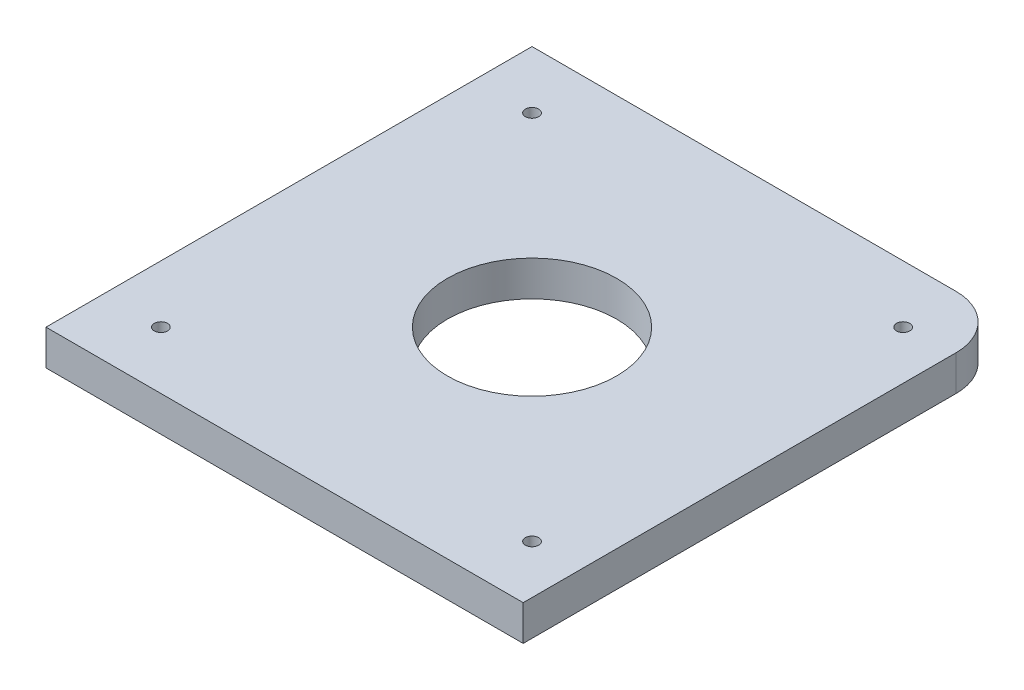
SolidWorks part; units mm, degrees
ref_plane "Front Plane" through (0, 0, 0) normal (0, 0, 1) x (1, 0, 0)
ref_plane "Top Plane" through (0, 0, 0) normal (0, 1, 0) x (1, 0, 0)
ref_plane "Right Plane" through (0, 0, 0) normal (1, 0, 0) x (0, 0, -1)
sketch "Sketch1" plane through (0, 0, 0) normal (0, 1, 0) x (1, 0, 0)
  line L2 (-55, -55) -> (-55, 55)
  line L3 (-55, 55) -> (53, 55)
  line L9 (-42, 55) -> (-42, -55) construction
  line L10 (53, 55) -> (53, -55)
  line L15 (42, 55) -> (42, -55) construction
  line L16 (53, -55) -> (-55, -55)
  circle A16 centre (0, 0) radius 19.15
  circle A17 centre (0, 0) radius 50 construction
  circle A18 centre (-42, 42) radius 1.5
  circle A19 centre (42, 42) radius 1.5
  circle A20 centre (42, -42) radius 1.5
  circle A21 centre (-42, -42) radius 1.5
  point P48 (0, 0)
  dimension "D7" = 38.3
  dimension "D11" = 100
  dimension "D16" = 3
  dimension "D19" = 55
  dimension "D26" = 13
  dimension "D3" = 11
  dimension "D12" = 13
  dimension "D15" = 84
  dimension "D17" = 42
  dimension "D20" = 55
  dimension "D18" = 4
extrude "Boss-Extrude1" add sketch "Sketch1" along normal blind 8
fillet "Fillet1" radius 12 1 edges at (53, 4, -55)
